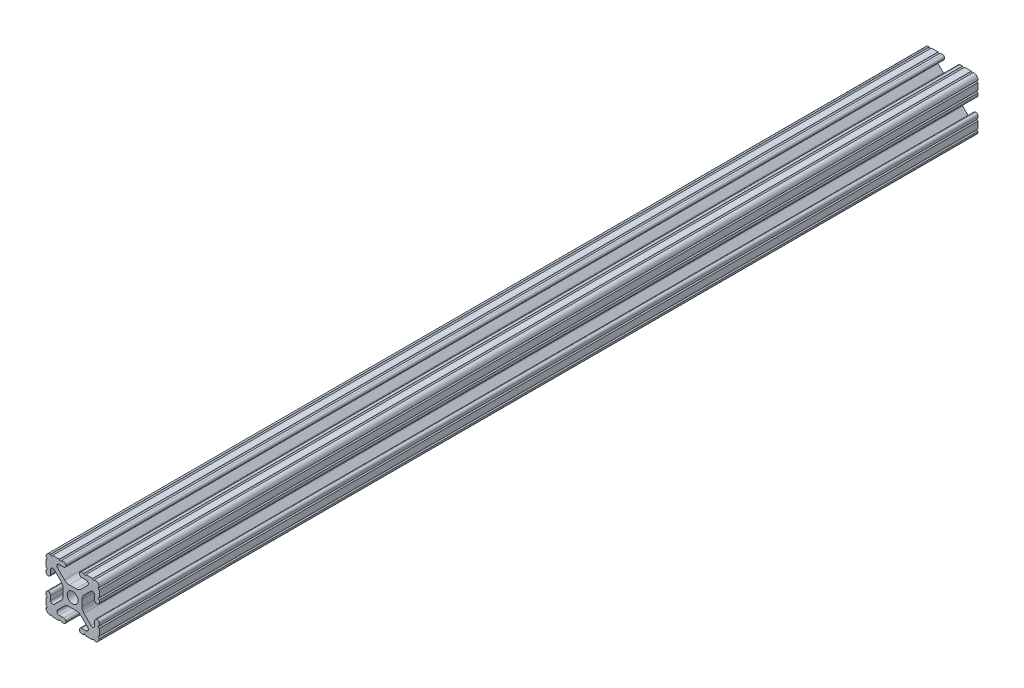
SolidWorks part; units mm, degrees
ref_plane "Front Plane" through (0, 0, 0) normal (0, 0, 1) x (1, 0, 0)
ref_plane "Top Plane" through (0, 0, 0) normal (0, 1, 0) x (1, 0, 0)
ref_plane "Right Plane" through (0, 0, 0) normal (1, 0, 0) x (0, 0, -1)
sketch "Sketch1" plane through (0, 0, 0) normal (0, 0, 1) x (1, 0, 0)
  line L0 (-7.207, 8.7244) -> (-3.8983, 5.4232)
  line L1 (-4.2875, 10.4902) -> (-6.4768, 10.4902)
  line L2 (-3.2385, 11.651) -> (-3.2385, 11.5392)
  line L3 (-5.3171, 12.7) -> (-4.2875, 12.7)
  line L4 (0, 13.4005) -> (0, -14.8534) construction
  line L5 (12.7, 0) -> (-13.9989, 0) construction
  line L6 (-9.5504, 12.7) -> (-6.3331, 12.7)
  line L7 (-12.7, 6.3331) -> (-12.7, 9.5504)
  line L8 (-12.7, 4.2875) -> (-12.7, 5.3171)
  line L9 (-11.5392, 3.2385) -> (-11.651, 3.2385)
  line L10 (-10.4902, 6.4021) -> (-10.4902, 4.2875)
  line L11 (-5.441, 3.8408) -> (-8.7371, 7.1294)
  line L12 (-4.5085, -1.5932) -> (-4.5085, 1.5932)
  line L13 (-1.7093, -4.4958) -> (1.7093, -4.4958)
  line L14 (3.9523, -5.4237) -> (7.1797, -8.6452)
  line L15 (6.4164, -10.4902) -> (4.2875, -10.4902)
  line L16 (3.2385, -11.5392) -> (3.2385, -11.651)
  line L17 (4.2875, -12.7) -> (5.3171, -12.7)
  line L18 (6.3331, -12.7) -> (9.5504, -12.7)
  line L19 (12.7, -9.5504) -> (12.7, -6.3331)
  line L20 (12.7, -5.3171) -> (12.7, -4.2875)
  line L21 (11.651, -3.2385) -> (11.5392, -3.2385)
  line L22 (10.4902, -4.2875) -> (10.4902, -6.4021)
  line L23 (8.7371, -7.1294) -> (5.441, -3.8408)
  line L24 (4.5085, -1.5932) -> (4.5085, 1.5932)
  line L25 (5.441, 3.8408) -> (8.7371, 7.1294)
  line L26 (10.4902, 6.4021) -> (10.4902, 4.2875)
  line L27 (11.5392, 3.2385) -> (11.651, 3.2385)
  line L28 (12.7, 4.2875) -> (12.7, 5.3171)
  line L29 (12.7, 6.3331) -> (12.7, 9.5504)
  line L30 (9.5504, 12.7) -> (6.3331, 12.7)
  line L31 (5.3171, 12.7) -> (4.2875, 12.7)
  line L32 (3.2385, 11.651) -> (3.2385, 11.5392)
  line L33 (4.2875, 10.4902) -> (6.4768, 10.4902)
  line L34 (7.207, 8.7244) -> (3.8983, 5.4232)
  line L35 (1.6558, 4.4958) -> (-1.6558, 4.4958)
  line L36 (-8.7371, -7.1294) -> (-5.441, -3.8408)
  line L37 (-10.4902, -4.2875) -> (-10.4902, -6.4021)
  line L38 (-11.651, -3.2385) -> (-11.5392, -3.2385)
  line L39 (-12.7, -5.3171) -> (-12.7, -4.2875)
  line L40 (-12.7, -9.5504) -> (-12.7, -6.3331)
  line L41 (-6.3331, -12.7) -> (-9.5504, -12.7)
  line L42 (-4.2875, -12.7) -> (-5.3171, -12.7)
  line L43 (-3.2385, -11.5392) -> (-3.2385, -11.651)
  line L44 (-6.4164, -10.4902) -> (-4.2875, -10.4902)
  line L45 (-3.9523, -5.4237) -> (-7.1797, -8.6452)
  arc A0 (-7.207, 8.7244) -> (-6.4768, 10.4902) centre (-6.4768, 9.4563) cw
  arc A1 (-3.2385, 11.5392) -> (-4.2875, 10.4902) centre (-4.2875, 11.5392) cw
  arc A2 (-4.2875, 12.7) -> (-3.2385, 11.651) centre (-4.2875, 11.651) cw
  arc A3 (-5.3171, 12.7) -> (-6.3331, 12.7) centre (-5.8251, 12.7) cw
  arc A4 (-9.5504, 12.7) -> (-10.5664, 12.6998) centre (-10.0584, 12.7) cw
  arc A5 (-12.6998, 10.5664) -> (-10.5664, 12.6998) centre (-10.5918, 10.5918) cw
  arc A6 (-12.6998, 10.5664) -> (-12.7, 9.5504) centre (-12.7, 10.0584) cw
  arc A7 (-12.7, 6.3331) -> (-12.7, 5.3171) centre (-12.7, 5.8251) cw
  arc A8 (-11.651, 3.2385) -> (-12.7, 4.2875) centre (-11.651, 4.2875) cw
  arc A9 (-10.4902, 4.2875) -> (-11.5392, 3.2385) centre (-11.5392, 4.2875) cw
  circle A10 centre (0, 0) radius 2.6035
  arc A11 (-10.4902, 6.4021) -> (-8.7371, 7.1294) centre (-9.4628, 6.4021) cw
  arc A12 (-5.441, 3.8408) -> (-4.5085, 1.5932) centre (-7.6835, 1.5932) cw
  arc A13 (-4.5085, -1.5932) -> (-5.441, -3.8408) centre (-7.6835, -1.5932) cw
  arc A14 (-8.7371, -7.1294) -> (-10.4902, -6.4021) centre (-9.4628, -6.4021) cw
  arc A15 (-1.7093, -4.4958) -> (-3.9523, -5.4237) centre (-1.7093, -7.6708) ccw
  arc A16 (3.9523, -5.4237) -> (1.7093, -4.4958) centre (1.7093, -7.6708) ccw
  arc A17 (6.4164, -10.4902) -> (7.1797, -8.6452) centre (6.4164, -9.4098) ccw
  arc A18 (4.2875, -10.4902) -> (3.2385, -11.5392) centre (4.2875, -11.5392) ccw
  arc A19 (3.2385, -11.651) -> (4.2875, -12.7) centre (4.2875, -11.651) ccw
  arc A20 (6.3331, -12.7) -> (5.3171, -12.7) centre (5.8251, -12.7) ccw
  arc A21 (10.5664, -12.6998) -> (9.5504, -12.7) centre (10.0584, -12.7) ccw
  arc A22 (10.5664, -12.6998) -> (12.6998, -10.5664) centre (10.5918, -10.5918) ccw
  arc A23 (12.7, -9.5504) -> (12.6998, -10.5664) centre (12.7, -10.0584) ccw
  arc A24 (12.7, -5.3171) -> (12.7, -6.3331) centre (12.7, -5.8251) ccw
  arc A25 (12.7, -4.2875) -> (11.651, -3.2385) centre (11.651, -4.2875) ccw
  arc A26 (11.5392, -3.2385) -> (10.4902, -4.2875) centre (11.5392, -4.2875) ccw
  arc A27 (8.7371, -7.1294) -> (10.4902, -6.4021) centre (9.4628, -6.4021) ccw
  arc A28 (4.5085, -1.5932) -> (5.441, -3.8408) centre (7.6835, -1.5932) ccw
  arc A29 (5.441, 3.8408) -> (4.5085, 1.5932) centre (7.6835, 1.5932) ccw
  arc A30 (10.4902, 6.4021) -> (8.7371, 7.1294) centre (9.4628, 6.4021) ccw
  arc A31 (10.4902, 4.2875) -> (11.5392, 3.2385) centre (11.5392, 4.2875) ccw
  arc A32 (11.651, 3.2385) -> (12.7, 4.2875) centre (11.651, 4.2875) ccw
  arc A33 (12.7, 6.3331) -> (12.7, 5.3171) centre (12.7, 5.8251) ccw
  arc A34 (12.6998, 10.5664) -> (12.7, 9.5504) centre (12.7, 10.0584) ccw
  arc A35 (12.6998, 10.5664) -> (10.5664, 12.6998) centre (10.5918, 10.5918) ccw
  arc A36 (9.5504, 12.7) -> (10.5664, 12.6998) centre (10.0584, 12.7) ccw
  arc A37 (5.3171, 12.7) -> (6.3331, 12.7) centre (5.8251, 12.7) ccw
  arc A38 (4.2875, 12.7) -> (3.2385, 11.651) centre (4.2875, 11.651) ccw
  arc A39 (3.2385, 11.5392) -> (4.2875, 10.4902) centre (4.2875, 11.5392) ccw
  arc A40 (7.207, 8.7244) -> (6.4768, 10.4902) centre (6.4768, 9.4563) ccw
  arc A41 (1.6558, 4.4958) -> (3.8983, 5.4232) centre (1.6558, 7.6708) ccw
  arc A42 (-1.6558, 4.4958) -> (-3.8983, 5.4232) centre (-1.6558, 7.6708) cw
  arc A43 (-11.5392, -3.2385) -> (-10.4902, -4.2875) centre (-11.5392, -4.2875) cw
  arc A44 (-12.7, -4.2875) -> (-11.651, -3.2385) centre (-11.651, -4.2875) cw
  arc A45 (-12.7, -5.3171) -> (-12.7, -6.3331) centre (-12.7, -5.8251) cw
  arc A46 (-12.7, -9.5504) -> (-12.6998, -10.5664) centre (-12.7, -10.0584) cw
  arc A47 (-10.5664, -12.6998) -> (-12.6998, -10.5664) centre (-10.5918, -10.5918) cw
  arc A48 (-10.5664, -12.6998) -> (-9.5504, -12.7) centre (-10.0584, -12.7) cw
  arc A49 (-6.3331, -12.7) -> (-5.3171, -12.7) centre (-5.8251, -12.7) cw
  arc A50 (-3.2385, -11.651) -> (-4.2875, -12.7) centre (-4.2875, -11.651) cw
  arc A51 (-4.2875, -10.4902) -> (-3.2385, -11.5392) centre (-4.2875, -11.5392) cw
  arc A52 (-6.4164, -10.4902) -> (-7.1797, -8.6452) centre (-6.4164, -9.4098) cw
  dimension "D1" = 5.207
  dimension "D9" = 14.859
  dimension "D2" = 25.4
  dimension "D3" = 12.7
  dimension "D4" = 6.477
  dimension "D5" = 8.2042
  dimension "D6" = 9.017
  dimension "D8" = 2.2098
  dimension "D10" = 2.2098
extrude "Extrude1" add sketch "Sketch1" against normal blind 419.1
